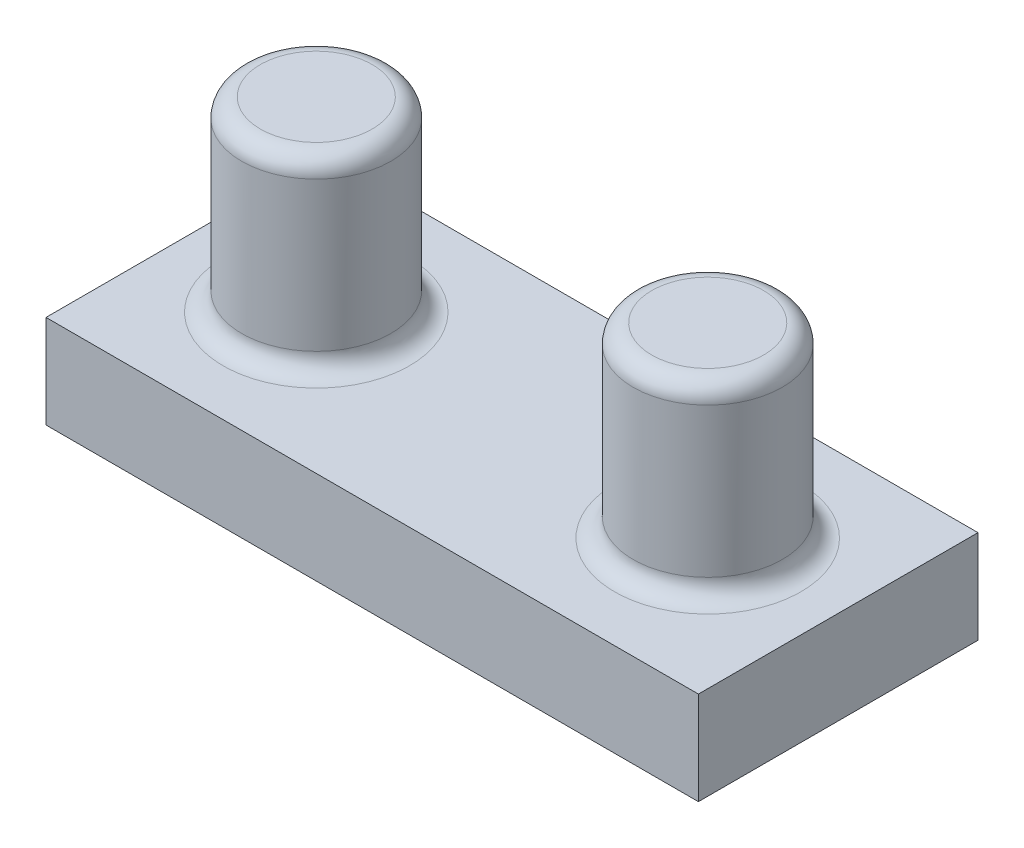
SolidWorks part; units mm, degrees
ref_plane "Front Plane" through (0, 0, 0) normal (0, 0, 1) x (1, 0, 0)
ref_plane "Top Plane" through (0, 0, 0) normal (0, 1, 0) x (1, 0, 0)
ref_plane "Right Plane" through (0, 0, 0) normal (1, 0, 0) x (0, 0, -1)
sketch "Sketch1" plane through (0, 0, 0) normal (0, 1, 0) x (1, 0, 0)
  line L0 (34.9998, 7.1697) -> (-26.696, 7.1697) construction
  circle A0 centre (10.0867, 7.1697) radius 4
  circle A1 centre (-10.9133, 7.1697) radius 4
  point P6 (0, 0)
  dimension "D1" = 21
  dimension "D2" = 8
  dimension "D3" = 8
extrude "Boss-Extrude1" add sketch "Sketch1" along normal blind 10
sketch "Sketch2" plane through (0, 0, 0) normal (0, -1, 0) x (-1, 0, 0)
  line L1 (17.9133, -0.3303) -> (-17.0867, -0.3303)
  line L2 (17.9133, -0.3303) -> (17.9133, 14.6697)
  line L3 (17.9133, 14.6697) -> (-17.0867, 14.6697)
  line L4 (-17.0867, -0.3303) -> (-17.0867, 14.6697)
  circle A0 centre (10.9133, 7.1697) radius 4 construction
  dimension "D1" = 35
  dimension "D2" = 7
  dimension "D3" = 15
  dimension "D4" = 7.5
extrude "Boss-Extrude2" add sketch "Sketch2" along normal blind 5
fillet "Fillet1" radius 1 4 edges at (-10.9133, 0, -11.1697) (10.0867, 0, -3.1697) (-10.9133, 10, -3.1697) (10.0867, 10, -3.1697)
sketch "Sketch3" plane through (0, 0, -14.6697) normal (0, 0, -1) x (-1, 0, 0)
  line L0 (15.3805, -4.4112) -> (-14.2204, -4.4112) construction
  text T0 "21 mm"
extrude "Cut-Extrude1" cut sketch "Sketch3" against normal blind 1
